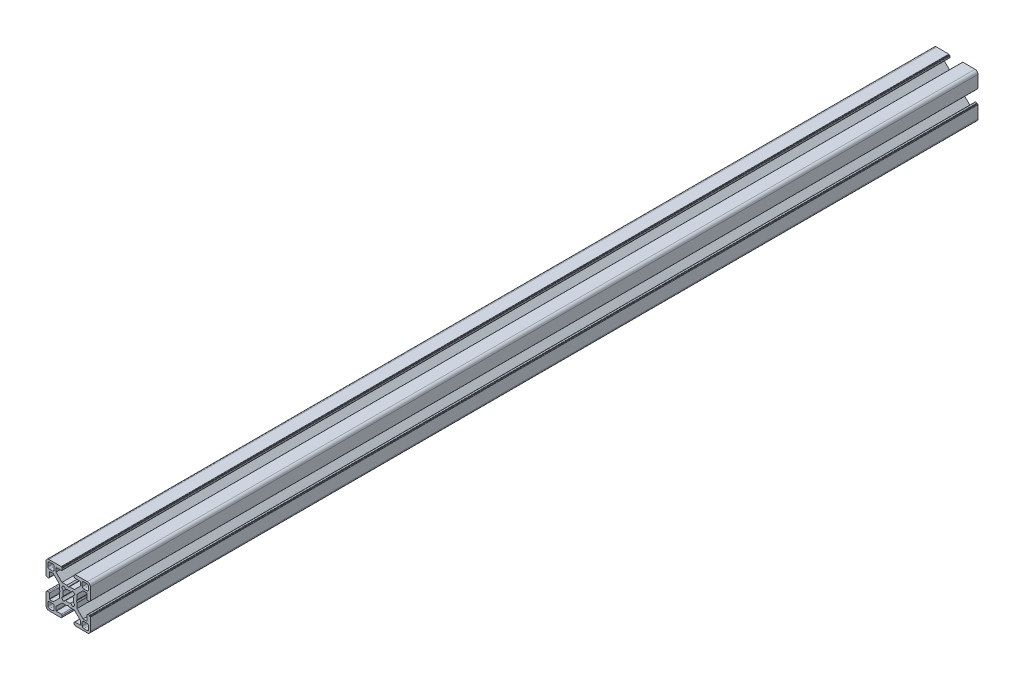
SolidWorks part; units mm, degrees
material "1060 Alloy"
ref_plane "Front" through (0, 0, 0) normal (0, 0, 1) x (1, 0, 0)
ref_plane "Top" through (0, 0, 0) normal (0, 1, 0) x (1, 0, 0)
ref_plane "Right" through (0, 0, 0) normal (1, 0, 0) x (0, 0, -1)
ref_plane "Plane1" through (0, 0, 25) normal (0, 0, 1) x (1, 0, 0)
sketch "Sketch1" plane through (0, 0, 25) normal (0, 0, 1) x (1, 0, 0)
  line L0 (-12.7, 13.7) -> (-10.5, 13.7)
  line L1 (-9.5, 12.7) -> (-9.5, 10.5)
  line L2 (-10.5, 9.5) -> (-12.7, 9.5)
  line L3 (-13.7, 10.5) -> (-13.7, 12.7)
  line L4 (-10.5, -13.7) -> (-12.7, -13.7)
  line L5 (-13.7, -12.7) -> (-13.7, -10.5)
  line L6 (-12.7, -9.5) -> (-10.5, -9.5)
  line L7 (-9.5, -10.5) -> (-9.5, -12.7)
  line L8 (10.5, 13.7) -> (12.7, 13.7)
  line L9 (13.7, 12.7) -> (13.7, 10.5)
  line L10 (12.7, 9.5) -> (10.5, 9.5)
  line L11 (9.5, 10.5) -> (9.5, 12.7)
  line L12 (13.7, -10.5) -> (13.7, -12.7)
  line L13 (12.7, -13.7) -> (10.5, -13.7)
  line L14 (9.5, -12.7) -> (9.5, -10.5)
  line L15 (10.5, -9.5) -> (12.7, -9.5)
  line L16 (-3.1359, 4.5184) -> (-1.6001, 3.2806)
  line L17 (1.6001, 3.2806) -> (3.1359, 4.5184)
  line L18 (4.5053, 3.1547) -> (3.2806, 1.6001)
  line L19 (3.2806, -1.6001) -> (4.5053, -3.1547)
  line L20 (3.1359, -4.5184) -> (1.6001, -3.2806)
  line L21 (-1.6001, -3.2806) -> (-3.1359, -4.5184)
  line L22 (-4.5053, -3.1547) -> (-3.2806, -1.6001)
  line L23 (-3.2806, 1.6001) -> (-4.5053, 3.1547)
  line L24 (-4.05, 13.4) -> (-4.05, 14.3)
  line L25 (-4.25, 14.5) -> (-4.35, 14.5)
  line L26 (-4.55, 14.7) -> (-4.55, 14.8)
  line L27 (-4.75, 15) -> (-13, 15)
  line L28 (-15, 13) -> (-15, 4.75)
  line L29 (-14.8, 4.55) -> (-14.7, 4.55)
  line L30 (-14.5, 4.35) -> (-14.5, 4.25)
  line L31 (-14.3, 4.05) -> (-13.4, 4.05)
  line L32 (-12.8, 4.65) -> (-12.8, 8.05)
  line L33 (-12.6, 8.25) -> (-10.05, 8.25)
  line L34 (-10.05, 8.25) -> (-6.0045, 4.2045)
  line L35 (-6.0045, 4.2045) -> (-6.0045, 0.9)
  line L36 (-6.0045, 0.9) -> (-5.4849, 0)
  line L37 (-5.4849, 0) -> (-6.0045, -0.9)
  line L38 (-6.0045, -0.9) -> (-6.0045, -4.2045)
  line L39 (-6.0045, -4.2045) -> (-10.05, -8.25)
  line L40 (-10.05, -8.25) -> (-12.6, -8.25)
  line L41 (-12.8, -8.05) -> (-12.8, -4.65)
  line L42 (-13.4, -4.05) -> (-14.3, -4.05)
  line L43 (-14.5, -4.25) -> (-14.5, -4.35)
  line L44 (-14.7, -4.55) -> (-14.8, -4.55)
  line L45 (-15, -4.75) -> (-15, -13)
  line L46 (-13, -15) -> (-4.75, -15)
  line L47 (-4.55, -14.8) -> (-4.55, -14.7)
  line L48 (-4.35, -14.5) -> (-4.25, -14.5)
  line L49 (-4.05, -14.3) -> (-4.05, -13.4)
  line L50 (-4.65, -12.8) -> (-8.05, -12.8)
  line L51 (-8.25, -12.6) -> (-8.25, -10.05)
  line L52 (-8.25, -10.05) -> (-4.2045, -6)
  line L53 (-4.2045, -6) -> (-0.9, -6)
  line L54 (-0.9, -6) -> (0, -5.4849)
  line L55 (0, -5.4849) -> (0.9, -6)
  line L56 (0.9, -6) -> (4.2045, -6)
  line L57 (4.2045, -6) -> (8.25, -10.05)
  line L58 (8.25, -10.05) -> (8.25, -12.6)
  line L59 (8.05, -12.8) -> (4.65, -12.8)
  line L60 (4.05, -13.4) -> (4.05, -14.3)
  line L61 (4.25, -14.5) -> (4.35, -14.5)
  line L62 (4.55, -14.7) -> (4.55, -14.8)
  line L63 (4.75, -15) -> (13, -15)
  line L64 (15, -13) -> (15, -4.75)
  line L65 (14.8, -4.55) -> (14.7, -4.55)
  line L66 (14.5, -4.35) -> (14.5, -4.25)
  line L67 (14.3, -4.05) -> (13.4, -4.05)
  line L68 (12.8, -4.65) -> (12.8, -8.05)
  line L69 (12.6, -8.25) -> (10.05, -8.25)
  line L70 (10.05, -8.25) -> (6.0045, -4.2045)
  line L71 (6.0045, -4.2045) -> (6.0045, -0.9)
  line L72 (6.0045, -0.9) -> (5.4849, 0)
  line L73 (5.4849, 0) -> (6.0045, 0.9)
  line L74 (6.0045, 0.9) -> (6.0045, 4.2045)
  line L75 (6.0045, 4.2045) -> (10.05, 8.25)
  line L76 (10.05, 8.25) -> (12.6, 8.25)
  line L77 (12.8, 8.05) -> (12.8, 4.65)
  line L78 (13.4, 4.05) -> (14.3, 4.05)
  line L79 (14.5, 4.25) -> (14.5, 4.35)
  line L80 (14.7, 4.55) -> (14.8, 4.55)
  line L81 (15, 4.75) -> (15, 13)
  line L82 (13, 15) -> (4.75, 15)
  line L83 (4.55, 14.8) -> (4.55, 14.7)
  line L84 (4.35, 14.5) -> (4.25, 14.5)
  line L85 (4.05, 14.3) -> (4.05, 13.4)
  line L86 (4.65, 12.8) -> (8.05, 12.8)
  line L87 (8.25, 12.6) -> (8.25, 10.05)
  line L88 (8.25, 10.05) -> (4.2045, 6)
  line L89 (4.2045, 6) -> (0.9, 6)
  line L90 (0.9, 6) -> (0, 5.4849)
  line L91 (0, 5.4849) -> (-0.9, 6)
  line L92 (-0.9, 6) -> (-4.2045, 6)
  line L93 (-4.2045, 6) -> (-8.25, 10.05)
  line L94 (-8.25, 10.05) -> (-8.25, 12.6)
  line L95 (-8.05, 12.8) -> (-4.65, 12.8)
  arc A0 (-13.7, 12.7) -> (-12.7, 13.7) centre (-12.7, 12.7) cw
  arc A1 (-10.5, 13.7) -> (-9.5, 12.7) centre (-10.5, 12.7) cw
  arc A2 (-9.5, 10.5) -> (-10.5, 9.5) centre (-10.5, 10.5) cw
  arc A3 (-12.7, 9.5) -> (-13.7, 10.5) centre (-12.7, 10.5) cw
  arc A4 (-9.5, -12.7) -> (-10.5, -13.7) centre (-10.5, -12.7) cw
  arc A5 (-12.7, -13.7) -> (-13.7, -12.7) centre (-12.7, -12.7) cw
  arc A6 (-13.7, -10.5) -> (-12.7, -9.5) centre (-12.7, -10.5) cw
  arc A7 (-10.5, -9.5) -> (-9.5, -10.5) centre (-10.5, -10.5) cw
  arc A8 (9.5, 12.7) -> (10.5, 13.7) centre (10.5, 12.7) cw
  arc A9 (12.7, 13.7) -> (13.7, 12.7) centre (12.7, 12.7) cw
  arc A10 (13.7, 10.5) -> (12.7, 9.5) centre (12.7, 10.5) cw
  arc A11 (10.5, 9.5) -> (9.5, 10.5) centre (10.5, 10.5) cw
  arc A12 (13.7, -12.7) -> (12.7, -13.7) centre (12.7, -12.7) cw
  arc A13 (10.5, -13.7) -> (9.5, -12.7) centre (10.5, -12.7) cw
  arc A14 (9.5, -10.5) -> (10.5, -9.5) centre (10.5, -10.5) cw
  arc A15 (12.7, -9.5) -> (13.7, -10.5) centre (12.7, -10.5) cw
  arc A16 (-4.5053, 3.1547) -> (-3.1359, 4.5184) centre (0, 0) cw
  arc A17 (-1.6001, 3.2806) -> (1.6001, 3.2806) centre (0, 0) cw
  arc A18 (3.1359, 4.5184) -> (4.5053, 3.1547) centre (0, 0) cw
  arc A19 (3.2806, 1.6001) -> (3.2806, -1.6001) centre (0, 0) cw
  arc A20 (4.5053, -3.1547) -> (3.1359, -4.5184) centre (0, 0) cw
  arc A21 (1.6001, -3.2806) -> (-1.6001, -3.2806) centre (0, 0) cw
  arc A22 (-3.1359, -4.5184) -> (-4.5053, -3.1547) centre (0, 0) cw
  arc A23 (-3.2806, -1.6001) -> (-3.2806, 1.6001) centre (0, 0) cw
  arc A24 (-4.65, 12.8) -> (-4.05, 13.4) centre (-4.65, 13.4) ccw
  arc A25 (-4.05, 14.3) -> (-4.25, 14.5) centre (-4.25, 14.3) ccw
  arc A26 (-4.35, 14.5) -> (-4.55, 14.7) centre (-4.35, 14.7) cw
  arc A27 (-4.55, 14.8) -> (-4.75, 15) centre (-4.75, 14.8) ccw
  arc A28 (-13, 15) -> (-15, 13) centre (-13, 13) ccw
  arc A29 (-15, 4.75) -> (-14.8, 4.55) centre (-14.8, 4.75) ccw
  arc A30 (-14.7, 4.55) -> (-14.5, 4.35) centre (-14.7, 4.35) cw
  arc A31 (-14.5, 4.25) -> (-14.3, 4.05) centre (-14.3, 4.25) ccw
  arc A32 (-13.4, 4.05) -> (-12.8, 4.65) centre (-13.4, 4.65) ccw
  arc A33 (-12.8, 8.05) -> (-12.6, 8.25) centre (-12.6, 8.05) cw
  arc A34 (-12.6, -8.25) -> (-12.8, -8.05) centre (-12.6, -8.05) cw
  arc A35 (-12.8, -4.65) -> (-13.4, -4.05) centre (-13.4, -4.65) ccw
  arc A36 (-14.3, -4.05) -> (-14.5, -4.25) centre (-14.3, -4.25) ccw
  arc A37 (-14.5, -4.35) -> (-14.7, -4.55) centre (-14.7, -4.35) cw
  arc A38 (-14.8, -4.55) -> (-15, -4.75) centre (-14.8, -4.75) ccw
  arc A39 (-15, -13) -> (-13, -15) centre (-13, -13) ccw
  arc A40 (-4.75, -15) -> (-4.55, -14.8) centre (-4.75, -14.8) ccw
  arc A41 (-4.55, -14.7) -> (-4.35, -14.5) centre (-4.35, -14.7) cw
  arc A42 (-4.25, -14.5) -> (-4.05, -14.3) centre (-4.25, -14.3) ccw
  arc A43 (-4.05, -13.4) -> (-4.65, -12.8) centre (-4.65, -13.4) ccw
  arc A44 (-8.05, -12.8) -> (-8.25, -12.6) centre (-8.05, -12.6) cw
  arc A45 (8.25, -12.6) -> (8.05, -12.8) centre (8.05, -12.6) cw
  arc A46 (4.65, -12.8) -> (4.05, -13.4) centre (4.65, -13.4) ccw
  arc A47 (4.05, -14.3) -> (4.25, -14.5) centre (4.25, -14.3) ccw
  arc A48 (4.35, -14.5) -> (4.55, -14.7) centre (4.35, -14.7) cw
  arc A49 (4.55, -14.8) -> (4.75, -15) centre (4.75, -14.8) ccw
  arc A50 (13, -15) -> (15, -13) centre (13, -13) ccw
  arc A51 (15, -4.75) -> (14.8, -4.55) centre (14.8, -4.75) ccw
  arc A52 (14.7, -4.55) -> (14.5, -4.35) centre (14.7, -4.35) cw
  arc A53 (14.5, -4.25) -> (14.3, -4.05) centre (14.3, -4.25) ccw
  arc A54 (13.4, -4.05) -> (12.8, -4.65) centre (13.4, -4.65) ccw
  arc A55 (12.8, -8.05) -> (12.6, -8.25) centre (12.6, -8.05) cw
  arc A56 (12.6, 8.25) -> (12.8, 8.05) centre (12.6, 8.05) cw
  arc A57 (12.8, 4.65) -> (13.4, 4.05) centre (13.4, 4.65) ccw
  arc A58 (14.3, 4.05) -> (14.5, 4.25) centre (14.3, 4.25) ccw
  arc A59 (14.5, 4.35) -> (14.7, 4.55) centre (14.7, 4.35) cw
  arc A60 (14.8, 4.55) -> (15, 4.75) centre (14.8, 4.75) ccw
  arc A61 (15, 13) -> (13, 15) centre (13, 13) ccw
  arc A62 (4.75, 15) -> (4.55, 14.8) centre (4.75, 14.8) ccw
  arc A63 (4.55, 14.7) -> (4.35, 14.5) centre (4.35, 14.7) cw
  arc A64 (4.25, 14.5) -> (4.05, 14.3) centre (4.25, 14.3) ccw
  arc A65 (4.05, 13.4) -> (4.65, 12.8) centre (4.65, 13.4) ccw
  arc A66 (8.05, 12.8) -> (8.25, 12.6) centre (8.05, 12.6) cw
  arc A67 (-8.25, 12.6) -> (-8.05, 12.8) centre (-8.05, 12.6) cw
extrude "Boss-Extrude1" add sketch "Sketch1" against normal blind 600
sketch "Sketch2" plane through (15, 0, 0) normal (1, 0, 0) x (0, 0, -1)
  line L0 (49, 15) -> (49, -15) construction
  line L1 (575, 15) -> (-25, 15) construction
  line L2 (575, -15) -> (-25, -15) construction
  line L3 (-25, 4.75) -> (-25, 13) construction
  line L4 (501, 15) -> (501, -15) construction
  line L5 (575, 4.75) -> (575, 13) construction
  circle A0 centre (49, 0) radius 3
  circle A1 centre (501, 0) radius 3
  dimension "D1" = 6
  dimension "D4" = 6
  dimension "D2" = 74
  dimension "D3" = 74
extrude "Cut-Extrude1" cut sketch "Sketch2" against normal through all
